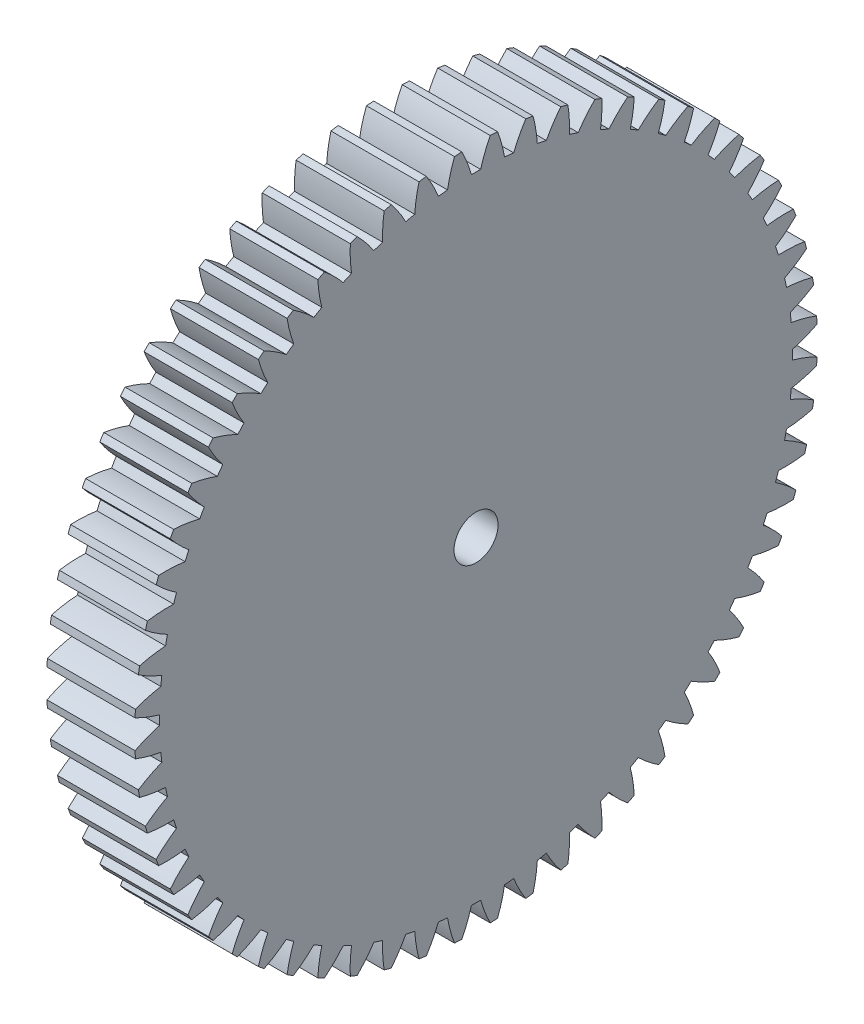
SolidWorks part; units mm, degrees
material "ABS"
ref_plane "Plane1" through (0, 0, 0) normal (0, 0, 1) x (1, 0, 0)
ref_plane "Plane2" through (0, 0, 0) normal (0, 1, 0) x (1, 0, 0)
ref_plane "Plane3" through (0, 0, 0) normal (1, 0, 0) x (0, 0, -1)
sketch "HoldingSke" plane through (0, 0, 0) normal (0, 1, 0) x (1, 0, 0)
  line L0 (0, 0) -> (2, -3.4641)
  line L1 (-15, 0) -> (100, 0) construction
  line L2 (0, 0) -> (-2.1039, 2.3779)
  line L3 (0, 0) -> (-11.863, 4.5341)
  line L4 (0, 0) -> (4.318, 7.479)
  line L5 (0, 0) -> (-46.8476, -17.4728)
  line L6 (0, 0) -> (-1.6579, -1.1186)
  line L7 (-2.1039, 2.3779) -> (8.6586, 51.2059)
  line L8 (-76.2, 54.61) -> (-76.1, 54.61)
  line L9 (-71.009, 38.7566) -> (-53.1078, 45.2721)
  line L10 (-76.2, 71.12) -> (104.1128, 71.12)
  line L11 (0, 0) -> (-2, 0)
  line L12 (-76.2, 101.6) -> (-76.192, 101.6)
  line L13 (24.9733, 27.94) -> (52.9518, 28.4284)
  line L14 (24.9733, 27.94) -> (24.9743, 27.94)
  line L15 (24.9733, 27.94) -> (100.4006, 29.5858)
  line L16 (-63.627, -0.25) -> (-12.827, -0.25)
  circle A0 centre (0, 0) radius 0.5
  circle A1 centre (0, 0) radius 7.1865
  circle A2 centre (0, 0) radius 37.5
  circle A3 centre (0, 0) radius 0.5
  dimension "MHD" = 14.373
  dimension "Hub_dia" = 75
  dimension "Bore" = 1
  dimension "MBD" = 1
  dimension "Num_teeth" = 60
  dimension "Pitch" = 4
  dimension "Overall_len" = 50
  dimension "Show_teeth" = 60
  dimension "Thickness" = 2
  dimension "OAL" = 50.0001
  dimension "T_dim" = 0.1
  dimension "Ap" = 20
  dimension "H" = 19.05
  dimension "Pitch_radius" = 180.3128
  dimension "Width" = 2
  dimension "Backlash" = 0.008
  dimension "Addendum_fac" = 1
  dimension "Dedendum_fac" = 1.25
  dimension "Clearance_fac" = 0.25
  dimension "Dedendum_add" = 0.001
  dimension "Module" = 0.25
sketch "BasProSke" plane through (0, 0, 0) normal (0, 1, 0) x (1, 0, 0)
  line L0 (-10, 0) -> (60, 0) construction
  line L1 (0, 0) -> (0, 7.75)
  line L2 (0, 0) -> (2, 0)
  line L3 (2, 0) -> (2, 7.75)
  line L4 (2, 7.75) -> (0, 7.75)
  dimension "Thickness" = 2
  dimension "Diameter" = 15.5
revolve "Base-Revolve" add sketch "BasProSke" angle 360 about L0
sketch "TooCutSke" plane through (0, 0, 0) normal (1, 0, 0) x (0, 0, -1)
  line L1 (0, 0) -> (0, 107) construction
  line L2 (0, 0) -> (-0.2103, 7.4971) construction
  line L3 (0, 0) -> (-0.7848, 14.975) construction
  line L4 (-0.2103, 7.4971) -> (-0.3924, 7.4875) construction
  arc A0 (0.1048, 7.1857) -> (-0.1048, 7.1857) centre (0, 0) ccw
  arc A1 (0.3351, 7.7682) -> (-0.3351, 7.7682) centre (0, 0) ccw
  circle A2 centre (0, 0) radius 7.5 construction
  circle A3 centre (0, 0) radius 7.0477 construction
  arc A4 (-0.1048, 7.1857) -> (-0.3351, 7.7682) centre (-2.9945, 6.3799) ccw
  arc A5 (0.3351, 7.7682) -> (0.1048, 7.1857) centre (2.9945, 6.3799) ccw
  dimension "Root_dia" = 14.373
  dimension "Overcut_dia" = 15.5508
  dimension "Pitch_dia" = 15
  dimension "Base_dia" = 14.0954
  dimension "Flank_rad" = 3
  dimension "Half_ang" = 3
  dimension "Half_CT" = 0.1823
extrude "ToothCut" cut sketch "TooCutSke" along normal through all
fillet "Breaks" [suppressed] radius 0.005
fillet "RootFillets" [suppressed] radius 0.0635
pattern_circular "TeethCuts" count 60 every 6 about axis through (-10, 0, 0) along (1, 0, 0) of "ToothCut", "RootFillets", "Breaks"
sketch "HubNeaOneSke" plane through (0, 0, 0) normal (-1, 0, 0) x (0, 0, 1)
  circle A0 centre (0, 0) radius 7.1865
  dimension "Diameter" = 14.373
extrude "HubNearOne" [suppressed] add sketch "HubNeaOneSke" along normal blind 48.0001
sketch "HubNeaBotSke" plane through (0, 0, 0) normal (-1, 0, 0) x (0, 0, 1)
  circle A0 centre (0, 0) radius 7.1865
  dimension "Diameter" = 14.373
extrude "HubNearBoth" [suppressed] add sketch "HubNeaBotSke" along normal blind 24
ref_plane "FarPln" through (2, 0, 0) normal (1, 0, 0) x (0, 0, -1)
sketch "HubFarSke" plane through (2, 0, 0) normal (1, 0, 0) x (0, 0, -1)
  circle A0 centre (0, 0) radius 7.1865
  dimension "Diameter" = 14.373
extrude "HubFar" [suppressed] add sketch "HubFarSke" along normal blind 24
sketch "BorSke" plane through (0, 0, 0) normal (1, 0, 0) x (0, 0, -1)
  circle A0 centre (0, 0) radius 0.5
  dimension "Diameter" = 1
extrude "Bore" cut sketch "BorSke" along normal mid plane 100.0001
sketch "KeySke" plane through (0, 0, 0) normal (1, 0, 0) x (0, 0, -1)
  line L0 (-0.05, 0) -> (-0.05, 0.6)
  line L1 (-0.05, 0.6) -> (0.05, 0.6)
  line L2 (0.05, 0.6) -> (0.05, 0)
  line L3 (0, 0) -> (0, 34) construction
  line L4 (-0.05, 0) -> (0.05, 0)
  dimension "Offset" = 0.6
  dimension "Width" = 0.1
extrude "Keyway" [suppressed] cut sketch "KeySke" along normal mid plane 100.0001
pattern_circular "Keyway2" [suppressed] count 2 every 90 about axis through (-10, 0, 0) along (1, 0, 0)
sketch "Sketch1" plane through (0, 0, 0) normal (1, 0, 0) x (0, 0, -1)
  circle A0 centre (0, 0) radius 1.5
  dimension "D1" = 3
extrude "Cut-Extrude1" cut sketch "Sketch1" along normal blind 1
equation "' \"Module@HoldingSke\" = 6.35"
equation "' \"Num_teeth@HoldingSke\" = 12"
equation "' \"Ap@HoldingSke\" =  20"
equation "' \"Ap@HoldingSke\" = 20"
equation "' \"Width@HoldingSke\" = 0.5 * 25.4"
equation "' \"Hub_dia@HoldingSke\"= 1 * 25.4"
equation "' \"Hub_dia@HoldingSke\" = 1 * 25.4"
equation "' \"Overall_len@HoldingSke\" = 1.0 * 25.4"
equation "' \"Bore@HoldingSke\" = 0.75 * 25.4"
equation "' \"T_dim@HoldingSke\" = 0.1 * 25.4"
equation "' \"Width@KeySke\" = 0.25 * 25.4"
equation "' \"Show_teeth@HoldingSke\" = 13"
equation "' \"Backlash@HoldingSke\" = 0.009 * 25.4"
equation "' \"Addendum_fac@HoldingSke\" = 1.0"
equation "' \"Dedendum_fac@HoldingSke\" = 1.25"
equation "' \"Dedendum_add@HoldingSke\" = 0.00005 * 25.4"
equation "' \"Clearance_fac@HoldingSke\" = 0.25"
equation "\"Pitch@HoldingSke\" = 1 / \"Module@HoldingSke\""
equation "\"Overcut_dia@TooCutSke\" = (\"Num_teeth@HoldingSke\" + 2 * \"Addendum_fac@HoldingSke\") / \"Pitch@HoldingSke\" + 0.002 * 25.4"
equation "\"Pitch_dia@TooCutSke\" = \"Num_teeth@HoldingSke\" / \"Pitch@HoldingSke\""
equation "\"Base_dia@TooCutSke\" = \"Num_teeth@HoldingSke\" / \"Pitch@HoldingSke\" * cos((\"Ap@HoldingSke\"  * 3.14159265 / 180))"
equation "\"Root_dia@TooCutSke\" = (\"Num_teeth@HoldingSke\" + 2) / \"Pitch@HoldingSke\" - 2 * (\"Addendum_fac@HoldingSke\" + \"Dedendum_fac@HoldingSke\") / \"Pitch@HoldingSke\" - \"Dedendum_add@HoldingSke\" * 2"
equation "\"Half_ang@TooCutSke\" = 180 / \"Num_teeth@HoldingSke\""
equation "\"Half_CT@TooCutSke\" = \"Num_teeth@HoldingSke\" / \"Pitch@HoldingSke\" * sin((3.14159265 / 2 / \"Num_teeth@HoldingSke\")) / 2 - 7 * \"Backlash@HoldingSke\" / 4"
equation "\"Flank_rad@TooCutSke\" = \"Num_teeth@HoldingSke\" / \"Pitch@HoldingSke\" / 5"
equation "\"Radius@RootFillets\" = \"Clearance_fac@HoldingSke\" / \"Pitch@HoldingSke\" + \"Dedendum_add@HoldingSke\""
equation "\"Break_rad@Breaks\" = 0.02 / \"Pitch@HoldingSke\""
equation "\"Thickness@HoldingSke\" = \"Width@HoldingSke\""
equation "\"OAL@HoldingSke\" = \"Thickness@HoldingSke\""
equation "\"MHD@HoldingSke\" = (\"Num_teeth@HoldingSke\" + 2) / \"Pitch@HoldingSke\" - 2 * (\"Addendum_fac@HoldingSke\" + \"Dedendum_fac@HoldingSke\")  / \"Pitch@HoldingSke\" - \"Dedendum_add@HoldingSke\" * 2"
equation "\"MBD@HoldingSke\" = (\"Num_teeth@HoldingSke\" + 2) / \"Pitch@HoldingSke\" - 2 * (\"Addendum_fac@HoldingSke\" + \"Dedendum_fac@HoldingSke\")  / \"Pitch@HoldingSke\" - \"Dedendum_add@HoldingSke\" * 2 - 0.002 * 25.4"
equation "\"MHD@HoldingSke\" = ((sgn( \"MHD@HoldingSke\" - \"Hub_dia@HoldingSke\" )-1)*( \"MHD@HoldingSke\" - \"Hub_dia@HoldingSke\" ))/-2+ \"Hub_dia@HoldingSke\""
equation "\"MBD@HoldingSke\" = ((sgn( \"MBD@HoldingSke\" - \"Bore@HoldingSke\" )-1)*( \"MBD@HoldingSke\" - \"Bore@HoldingSke\" ))/-2+ \"Bore@HoldingSke\""
equation "\"OAL@HoldingSke\" = ((sgn( \"OAL@HoldingSke\" - \"Overall_len@HoldingSke\" )+1)*( \"OAL@HoldingSke\" - \"Overall_len@HoldingSke\" ))/2 + \"Overall_len@HoldingSke\" + 0.000002 * 25.4"
equation "\"Num_teeth@TeethCuts\" = int( \"Show_teeth@HoldingSke\" ) + 1"
equation "\"Num_teeth@TeethCuts\" = ((sgn( \"Num_teeth@TeethCuts\" - \"Num_teeth@HoldingSke\" )-1)*( \"Num_teeth@TeethCuts\" - \"Num_teeth@HoldingSke\" ))/-2+ \"Num_teeth@HoldingSke\""
equation "\"Num_teeth@TeethCuts\" = ((sgn( \"Num_teeth@TeethCuts\" - 2.0)+1)*( \"Num_teeth@TeethCuts\" - 2.0))/2 +2.0"
equation "\"Angle@TeethCuts\" = 360.0 / \"Num_teeth@HoldingSke\""
equation "\"Diameter@BasProSke\" = (\"Num_teeth@HoldingSke\" + 2 * \"Addendum_fac@HoldingSke\") / \"Pitch@HoldingSke\""
equation "\"Thickness@BasProSke\"  = \"Thickness@HoldingSke\""
equation "' \"Fillet_rad@BasProSke\" =  \"Thickness@HoldingSke\" * 0.05"
equation "' \"Fillet_rad@BasProSke\" = \"Thickness@HoldingSke\" * 0.05"
equation "\"MHD@HoldingSke\" = ((sgn( \"MHD@HoldingSke\" - \"Root_dia@TooCutSke\" )-1)*( \"MHD@HoldingSke\" - \"Root_dia@TooCutSke\" ))/-2+ \"Root_dia@TooCutSke\""
equation "\"Diameter@HubNeaOneSke\" = \"MHD@HoldingSke\""
equation "\"Length@HubNearOne\" = \"OAL@HoldingSke\" - \"Thickness@BasProSke\""
equation "\"Diameter@HubNeaBotSke\" = \"MHD@HoldingSke\""
equation "\"Length@HubNearBoth\" = ( \"OAL@HoldingSke\" - \"Thickness@BasProSke\" ) / 2.0"
equation "\"Thickness@FarPln\" = \"Thickness@BasProSke\""
equation "\"Diameter@HubFarSke\" = \"MHD@HoldingSke\""
equation "\"Length@HubFar\" = ( \"OAL@HoldingSke\" - \"Thickness@BasProSke\" ) / 2.0"
equation "\"Diameter@BorSke\" = \"MBD@HoldingSke\""
equation "\"D1@Bore\" = \"OAL@HoldingSke\" * 2.0"
equation "\"D1@Keyway\" = \"OAL@HoldingSke\" * 2.0"
equation "\"Offset@KeySke\" = \"T_dim@HoldingSke\" + \"MBD@HoldingSke\" / 2.0"
